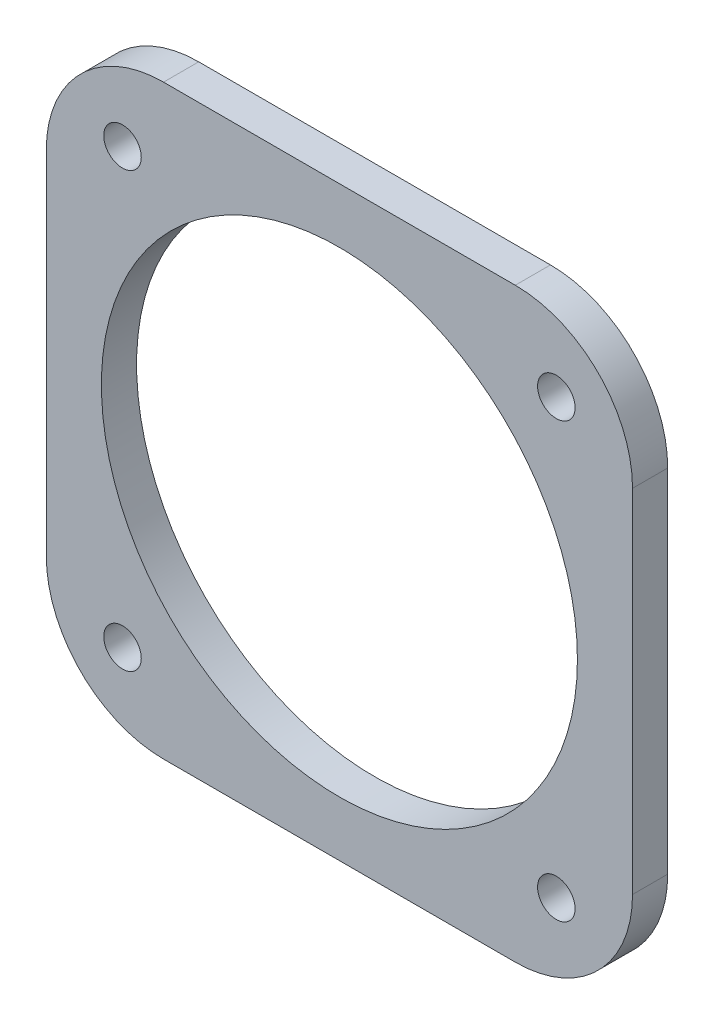
SolidWorks part; units mm, degrees
ref_plane "前视基准面" through (0, 0, 0) normal (0, 0, 1) x (1, 0, 0)
ref_plane "上视基准面" through (0, 0, 0) normal (0, 1, 0) x (1, 0, 0)
ref_plane "右视基准面" through (0, 0, 0) normal (1, 0, 0) x (0, 0, -1)
sketch "草图2" plane through (0, 0, 0) normal (0, 0, 1) x (1, 0, 0)
  line L1 (-18.5, 18.5) -> (18.5, 18.5) construction
  line L2 (-18.5, 18.5) -> (-18.5, -18.5) construction
  line L3 (-18.5, -18.5) -> (18.5, -18.5) construction
  line L4 (18.5, 18.5) -> (18.5, -18.5) construction
  line L5 (-18.5, 18.5) -> (18.5, -18.5) construction
  line L6 (-18.5, -18.5) -> (18.5, 18.5) construction
  line L7 (-25, 25) -> (25, 25)
  line L8 (-25, 25) -> (-25, -25)
  line L9 (-25, -25) -> (25, -25)
  line L10 (25, 25) -> (25, -25)
  line L11 (-25, 25) -> (25, -25) construction
  line L12 (-25, -25) -> (25, 25) construction
  circle A0 centre (-18.5, 18.5) radius 1.6
  circle A1 centre (18.5, 18.5) radius 1.6
  circle A2 centre (18.5, -18.5) radius 1.6
  circle A3 centre (-18.5, -18.5) radius 1.6
  circle A4 centre (0, 0) radius 21.5 construction
  circle A5 centre (0, 0) radius 20.3
  point P0 (0, 0)
  point P17 (0, 0)
  dimension "D1" = 37
  dimension "D3" = 4
  dimension "D4" = 3.2
  dimension "D5" = 43
  dimension "D6" = 40.6
  dimension "D2" = 37
  dimension "D7" = 50
  dimension "D8" = 50
extrude "凸台-拉伸1" add sketch "草图2" along normal blind 3
fillet "圆角1" radius 10 4 edges at (25, 25, 1.5) (25, -25, 1.5) (-25, -25, 1.5) (-25, 25, 1.5)
